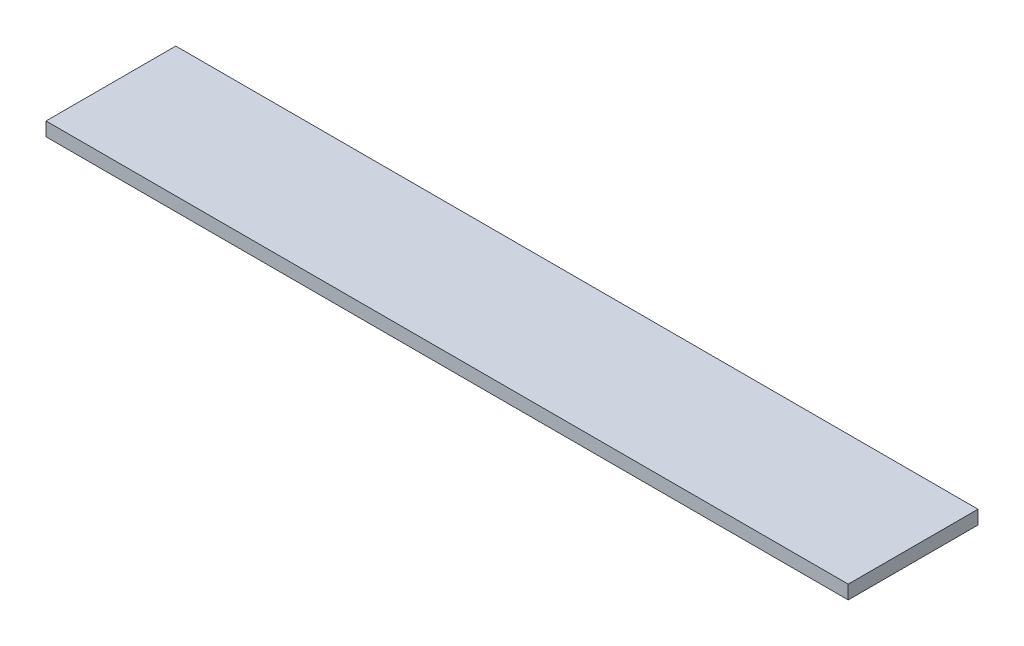
SolidWorks part; units mm, degrees
material "丙烯酸(中高冲击)"
ref_plane "Front" through (0, 0, 0) normal (0, 0, 1) x (1, 0, 0)
ref_plane "Top" through (0, 0, 0) normal (0, 1, 0) x (1, 0, 0)
ref_plane "Right" through (0, 0, 0) normal (1, 0, 0) x (0, 0, -1)
sketch "草图1" plane through (0, 0, 0) normal (0, 1, 0) x (1, 0, 0)
  line L1 (0, 0) -> (272, 0)
  line L2 (0, 0) -> (0, 44)
  line L3 (0, 44) -> (272, 44)
  line L4 (272, 0) -> (272, 44)
  dimension "D1" = 44
  dimension "D2" = 272
extrude "凸台-拉伸1" add sketch "草图1" along normal blind 4.65
